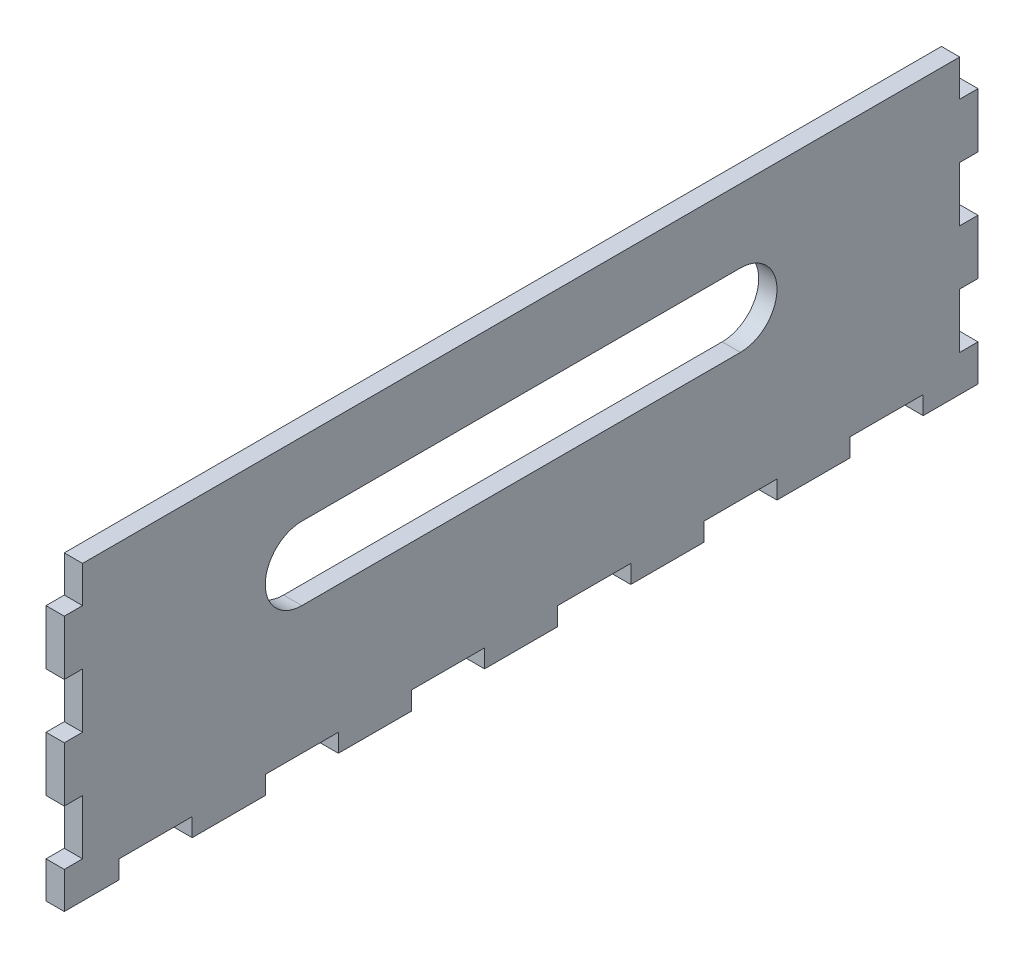
SolidWorks part; units mm, degrees
material "Oak"
ref_plane "Front Plane" through (0, 0, 0) normal (0, 0, 1) x (1, 0, 0)
ref_plane "Top Plane" through (0, 0, 0) normal (0, 1, 0) x (1, 0, 0)
ref_plane "Right Plane" through (0, 0, 0) normal (1, 0, 0) x (0, 0, -1)
sketch "Sketch2" plane through (0, 0, 0) normal (1, 0, 0) x (0, 0, -1)
  line L0 (-152.4, 101.6) -> (152.4, 101.6)
  line L1 (152.4, 101.6) -> (152.4, 88.9)
  line L2 (152.4, 88.9) -> (158.75, 88.9)
  line L3 (158.75, 88.9) -> (158.75, 69.85)
  line L4 (158.75, 69.85) -> (152.4, 69.85)
  line L5 (152.4, 69.85) -> (152.4, 50.8)
  line L6 (152.4, 50.8) -> (158.75, 50.8)
  line L7 (158.75, 50.8) -> (158.75, 31.75)
  line L8 (158.75, 0) -> (139.7, 0)
  line L9 (-158.75, 0) -> (-158.75, 12.7)
  line L10 (-158.75, 50.8) -> (-152.4, 50.8)
  line L11 (-152.4, 50.8) -> (-152.4, 69.85)
  line L12 (-152.4, 69.85) -> (-158.75, 69.85)
  line L13 (-158.75, 69.85) -> (-158.75, 88.9)
  line L14 (-158.75, 88.9) -> (-152.4, 88.9)
  line L15 (-152.4, 88.9) -> (-152.4, 101.6)
  line L16 (139.7, 0) -> (139.7, 6.35)
  line L17 (-76.2, 50.8) -> (76.2, 50.8)
  line L19 (-76.2, 76.2) -> (76.2, 76.2)
  line L21 (-76.2, 50.8) -> (76.2, 76.2) construction
  line L22 (-76.2, 76.2) -> (76.2, 50.8) construction
  line L23 (139.7, 6.35) -> (114.3, 6.35)
  line L24 (114.3, 6.35) -> (114.3, 0)
  line L25 (114.3, 0) -> (88.9, 0)
  line L26 (88.9, 0) -> (88.9, 6.35)
  line L27 (88.9, 6.35) -> (63.5, 6.35)
  line L28 (63.5, 6.35) -> (63.5, 0)
  line L29 (38.1, 0) -> (38.1, 6.35)
  line L30 (38.1, 6.35) -> (12.7, 6.35)
  line L31 (12.7, 6.35) -> (12.7, 0)
  line L32 (-12.7, 0) -> (-12.7, 6.35)
  line L33 (-12.7, 6.35) -> (-38.1, 6.35)
  line L34 (-38.1, 6.35) -> (-38.1, 0)
  line L35 (-63.5, 0) -> (-63.5, 6.35)
  line L36 (-63.5, 6.35) -> (-88.9, 6.35)
  line L37 (-88.9, 6.35) -> (-88.9, 0)
  line L38 (-114.3, 0) -> (-114.3, 6.35)
  line L39 (-114.3, 6.35) -> (-139.7, 6.35)
  line L40 (-139.7, 6.35) -> (-139.7, 0)
  line L41 (63.5, 0) -> (38.1, 0)
  line L42 (12.7, 0) -> (-12.7, 0)
  line L43 (-38.1, 0) -> (-63.5, 0)
  line L44 (-88.9, 0) -> (-114.3, 0)
  line L45 (-139.7, 0) -> (-158.75, 0)
  line L46 (-158.75, 31.75) -> (-152.4, 31.75)
  line L47 (-152.4, 31.75) -> (-152.4, 12.7)
  line L48 (-152.4, 12.7) -> (-158.75, 12.7)
  line L49 (-158.75, 31.75) -> (-158.75, 50.8)
  line L50 (0, 55) -> (0, -55) construction
  line L51 (152.4, 12.7) -> (158.75, 12.7)
  line L52 (152.4, 31.75) -> (152.4, 12.7)
  line L53 (158.75, 31.75) -> (152.4, 31.75)
  line L54 (158.75, 12.7) -> (158.75, 0)
  arc A0 (-76.2, 76.2) -> (-76.2, 50.8) centre (-76.2, 63.5) ccw
  arc A1 (76.2, 50.8) -> (76.2, 76.2) centre (76.2, 63.5) ccw
  point P2 (0, 63.5)
  dimension "D13" = 12.7
  dimension "D14" = 12.7
  dimension "D15" = 76.2
  dimension "D1" = 304.8
  dimension "D2" = 6.35
  dimension "D3" = 12.7
  dimension "D4" = 101.6
  dimension "D5" = 19.05
  dimension "D6" = 19.05
  dimension "D8" = 158.75
  dimension "D9" = 152.4
  dimension "D10" = 0
  dimension "D11" = 25.4
  dimension "D12" = 25.4
  dimension "D16" = 25.4
  dimension "D17" = 6.35
  dimension "D18" = 19.05
  dimension "D20" = 25.4
  dimension "D21" = 6.35
  dimension "D22" = 19.05
  dimension "D23" = 19.05
  dimension "D19" = 6
extrude "Boss-Extrude1" add sketch "Sketch2" along normal blind 6.35
